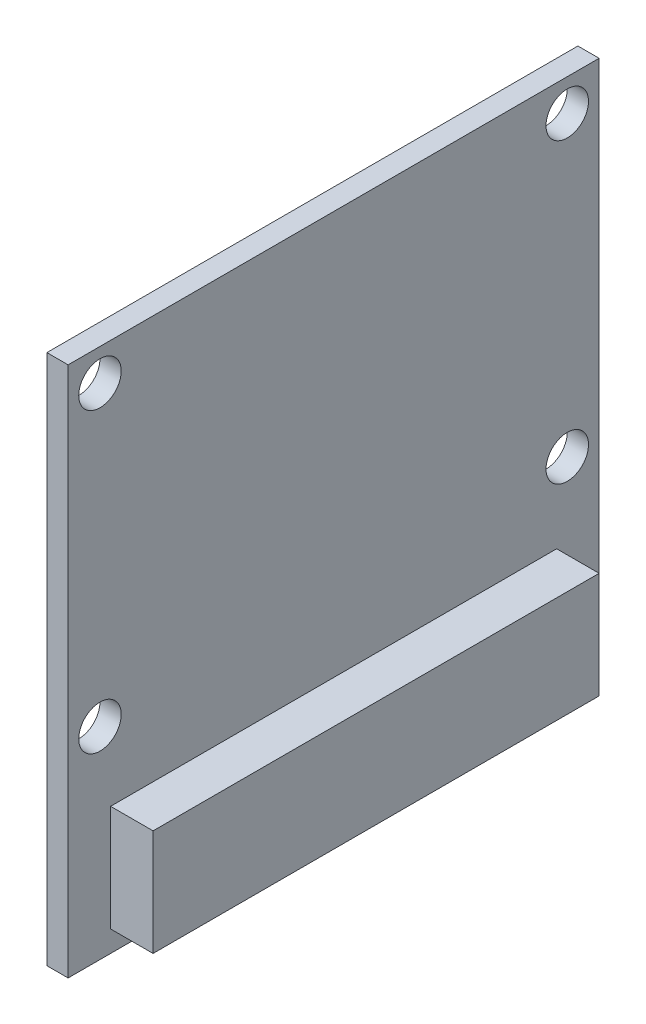
SolidWorks part; units mm, degrees
ref_plane "Front Plane" through (0, 0, 0) normal (0, 0, 1) x (1, 0, 0)
ref_plane "Top Plane" through (0, 0, 0) normal (0, 1, 0) x (1, 0, 0)
ref_plane "Right Plane" through (0, 0, 0) normal (1, 0, 0) x (0, 0, -1)
sketch "Sketch1" plane through (0, 0, 0) normal (1, 0, 0) x (0, 0, -1)
  line L1 (0, 0) -> (25, 0)
  line L2 (0, 0) -> (0, 25)
  line L3 (0, 25) -> (25, 25)
  line L4 (25, 0) -> (25, 25)
  dimension "D1" = 25
  dimension "D2" = 25
extrude "Boss-Extrude1" add sketch "Sketch1" along normal blind 1 contours L3 L4 L1 L2
sketch "Sketch2" plane through (1, 0, 0) normal (1, 0, 0) x (0, 0, -1)
  line L0 (0, 0) -> (25, 0) construction
  line L1 (2, 6) -> (23, 6)
  line L2 (2, 6) -> (2, 1)
  line L3 (2, 1) -> (23, 1)
  line L4 (23, 6) -> (23, 1)
  line L5 (0, 0) -> (0, 25) construction
  dimension "D1" = 21
  dimension "D2" = 5
  dimension "D3" = 1
  dimension "D4" = 2
extrude "Boss-Extrude2" add sketch "Sketch2" along normal blind 2
sketch "Sketch3" plane through (0, 0, 0) normal (-1, 0, 0) x (0, 0, 1)
  line L0 (0, 0) -> (0, 25) construction
  line L1 (-16.5, 14) -> (-8.5, 14)
  line L2 (-16.5, 14) -> (-16.5, 6)
  line L3 (-16.5, 6) -> (-8.5, 6)
  line L4 (-8.5, 14) -> (-8.5, 6)
  line L5 (-16.5, 14) -> (-8.5, 6) construction
  line L6 (-16.5, 6) -> (-8.5, 14) construction
  line L7 (0, 0) -> (-25, 0) construction
  point P0 (-12.5, 10)
  dimension "D1" = 8
  dimension "D2" = 8
  dimension "D3" = 8.5
  dimension "D4" = 6
extrude "Boss-Extrude3" add sketch "Sketch3" along normal blind 2
sketch "Sketch5" plane through (-2, 0, 0) normal (-1, 0, 0) x (0, 0, 1)
  circle A0 centre (-12.5, 10) radius 3.5
  dimension "D1" = 7
extrude "Boss-Extrude4" add sketch "Sketch5" along normal blind 1
sketch "Sketch6" plane through (0, 0, 0) normal (-1, 0, 0) x (0, 0, 1)
  line L0 (0, 0) -> (0, 25) construction
  line L1 (-16, 23.3639) -> (-9, 23.3639)
  line L2 (-16, 23.3639) -> (-16, 19.3639)
  line L3 (-16, 19.3639) -> (-15, 19.3639)
  line L4 (-9, 23.3639) -> (-9, 19.3639)
  line L5 (-8.5, 14) -> (-16.5, 14) construction
  line L7 (-15, 19.3639) -> (-15, 14)
  line L8 (-15, 14) -> (-10, 14)
  line L9 (-10, 19.3639) -> (-10, 14)
  line L10 (-10, 19.3639) -> (-9, 19.3639)
  dimension "D1" = 7
  dimension "D2" = 4
  dimension "D3" = 9
  dimension "D4" = 1
  dimension "D5" = 1
extrude "Boss-Extrude5" add sketch "Sketch6" along normal blind 1
sketch "Sketch7" plane through (0, 0, 0) normal (-1, 0, 0) x (0, 0, 1)
  line L0 (-25, 23.5) -> (0, 23.5) construction
  line L1 (-25, 0) -> (-25, 25) construction
  line L2 (0, 0) -> (0, 25) construction
  line L3 (0, 23.5) -> (-1.5, 25) construction
  line L4 (0, 25) -> (-25, 25) construction
  line L5 (-1.5, 25) -> (-1.5, 0) construction
  line L6 (0, 0) -> (-25, 0) construction
  line L7 (-1.5, 0) -> (-23.5, 0) construction
  line L8 (-23.5, 0) -> (-23.5, 25) construction
  line L9 (-25, 9.5) -> (0, 9.5) construction
  circle A0 centre (-23.5, 23.5) radius 1
  circle A1 centre (-1.5, 23.5) radius 1
  circle A2 centre (-1.5, 9.5) radius 1
  circle A3 centre (-23.5, 9.5) radius 1
  point P24 (0, 0)
  dimension "D5" = 2
  dimension "D1" = 1.5
  dimension "D2" = 1.5
  dimension "D3" = 1.5
  dimension "D4" = 9.5
  dimension "D6" = 1.5
  dimension "D7" = 1.5
extrude "Cut-Extrude1" cut sketch "Sketch7" against normal blind 1
